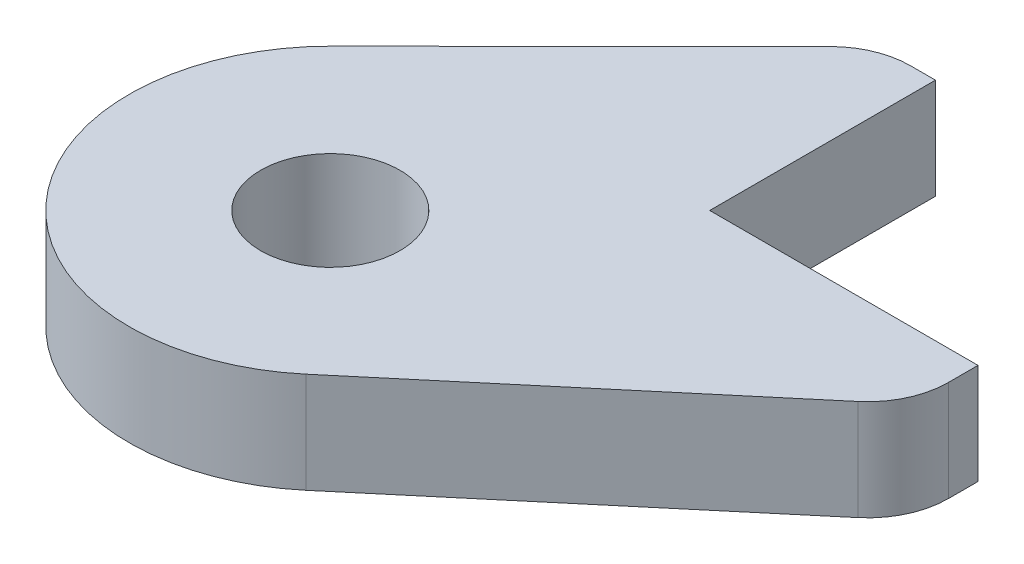
SolidWorks part; units mm, degrees
material "Alloy Steel"
ref_plane "X-Y Datum" through (0, 0, 0) normal (0, 0, 1) x (1, 0, 0)
ref_plane "X-Z Datum" through (0, 0, 0) normal (0, 1, 0) x (1, 0, 0)
ref_plane "Y-Z Datum" through (0, 0, 0) normal (1, 0, 0) x (0, 0, -1)
sketch "Sketch4" plane through (0, 0, 0) normal (0, 1, 0) x (1, 0, 0)
  line L1 (-12.7, -12.7) -> (12.7, -12.7) construction
  line L2 (-12.7, -12.7) -> (-12.7, 12.7) construction
  line L3 (-12.7, 12.7) -> (12.7, 12.7) construction
  line L4 (12.7, -12.7) -> (12.7, 12.7) construction
  line L5 (-12.7, -12.7) -> (12.7, 12.7) construction
  line L6 (-12.7, 12.7) -> (12.7, -12.7) construction
  line L8 (-12.7, -2.0139) -> (-12.7, -12.7)
  line L9 (-12.7, -12.7) -> (0, -12.7)
  line L10 (-12.7, -12.7) -> (-21.6803, -21.6803) construction
  line L12 (0, -12.7) -> (0, -15.875)
  line L13 (-12.7, -2.0139) -> (-15.4525, -2.0139)
  line L14 (-15.4525, -2.0139) -> (-28.4072, -14.9368)
  line L15 (0, -15.875) -> (-15.5447, -28.9659)
  circle A0 centre (-21.6803, -21.6803) radius 9.525 construction
  arc A3 (-28.4072, -14.9368) -> (-15.5447, -28.9659) centre (-21.6803, -21.6803) ccw
  point P0 (0, 0)
  dimension "D2" = 19.05
  dimension "D1" = 25.4
  dimension "D3" = 12.7
extrude "Boss-Extrude2" add sketch "Sketch4" along normal blind 4.7625
fillet "Fillet3" radius 3.81 2 edges at (0, 2.3813, 15.875) (-15.4525, 2.3813, 2.0139)
hole_wizard "M6 Clearance Hole3" positions "Sketch7" profile "Sketch8" hole size "M6" standard "ANSI Metric" end condition through all
sketch "Sketch7" plane through (0, 4.7625, 0) normal (0, 1, 0) x (1, 0, 0)
  point P0 (-21.6803, -21.6803)
sketch "Sketch8" plane through (-21.6803, 4.7625, 21.6803) normal (1, 0, 0) x (0, 0, 1)
  line L0 (0, 0) -> (0, 4.7625)
  line L1 (0, 4.7625) -> (3.3, 4.7625)
  line L2 (3.3, 4.7625) -> (3.3, 0)
  line L5 (3.3, 0) -> (0, 0)
  line L11 (0, -6.35) -> (0, 107.95) construction
  dimension "Thru Hole Dia." = 6.6
  dimension "Thru Hole Depth" = 4.7625
